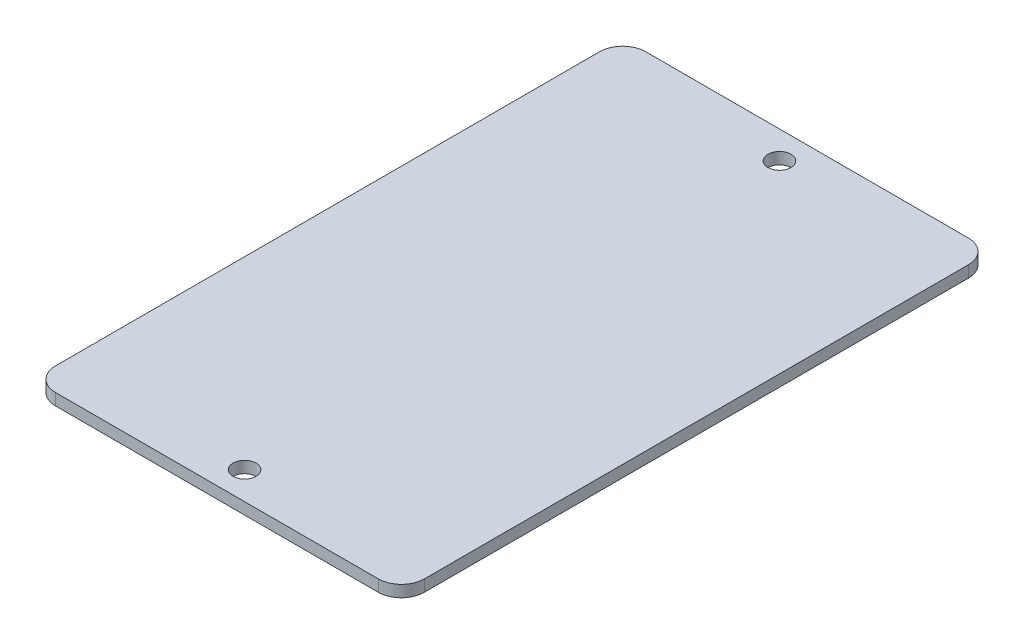
SolidWorks part; units mm, degrees
ref_plane "Front Plane" through (0, 0, 0) normal (0, 0, 1) x (1, 0, 0)
ref_plane "Top Plane" through (0, 0, 0) normal (0, 1, 0) x (1, 0, 0)
ref_plane "Right Plane" through (0, 0, 0) normal (1, 0, 0) x (0, 0, -1)
sketch "Sketch1" plane through (0, 0, 0) normal (0, 1, 0) x (1, 0, 0)
  line L1 (-25.4, -40.64) -> (25.4, -40.64)
  line L2 (-25.4, -40.64) -> (-25.4, 40.64)
  line L3 (-25.4, 40.64) -> (25.4, 40.64)
  line L4 (25.4, -40.64) -> (25.4, 40.64)
  line L5 (-25.4, -40.64) -> (25.4, 40.64) construction
  line L6 (-25.4, 40.64) -> (25.4, -40.64) construction
  point P0 (0, 0)
  dimension "D1" = 81.28
  dimension "D2" = 50.8
extrude "Boss-Extrude1" add sketch "Sketch1" along normal mid plane 1.6002
sketch "Sketch2" plane through (0, 0.8001, 0) normal (0, 1, 0) x (1, 0, 0)
  line L0 (0, 36.83) -> (0, -36.83) construction
  circle A0 centre (0, 36.83) radius 1.5875
  circle A1 centre (0, -36.83) radius 1.5875
  point P3 (0, 0)
  dimension "D1" = 3.175
  dimension "D2" = 73.66
extrude "Cut-Extrude1" cut sketch "Sketch2" against normal through all
fillet "Fillet1" radius 3.175 4 edges at (25.4, 0, 40.64) (-25.4, 0, 40.64) (25.4, 0, -40.64) (-25.4, 0, -40.64)
